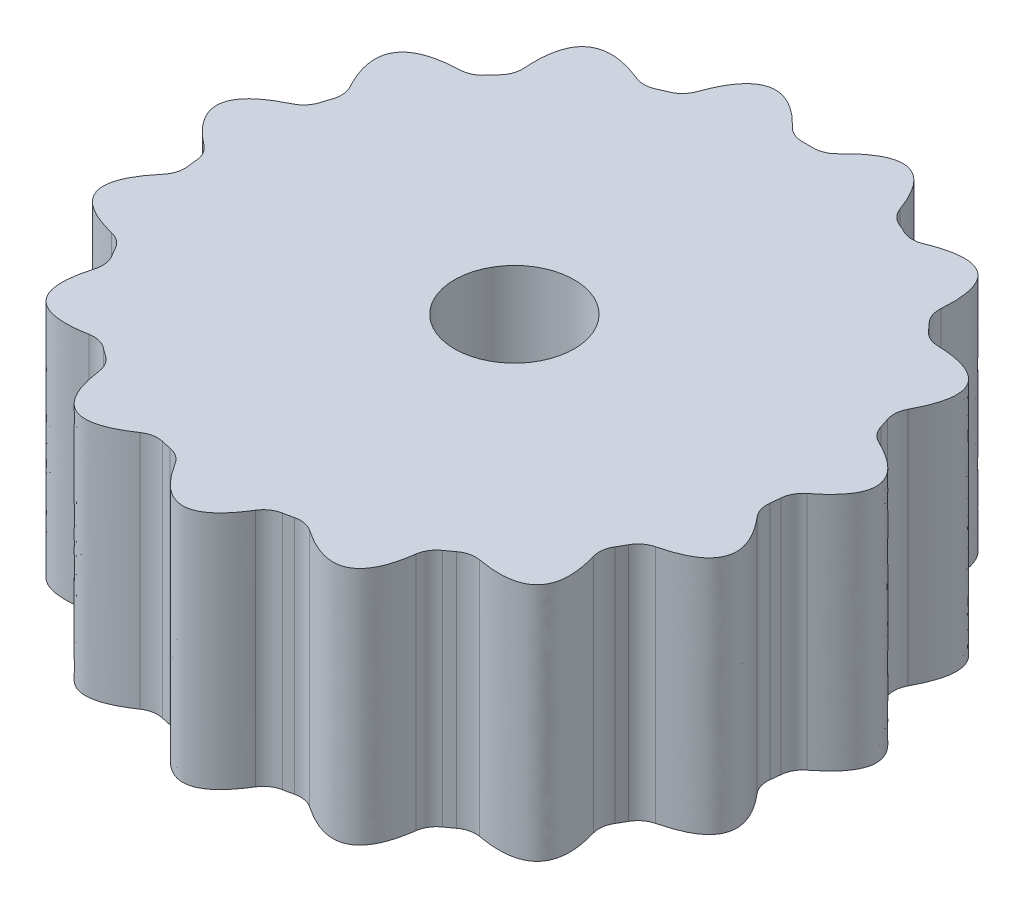
SolidWorks part; units mm, degrees
ref_plane "Front Plane" through (0, 0, 0) normal (0, 0, 1) x (1, 0, 0)
ref_plane "Top Plane" through (0, 0, 0) normal (0, 1, 0) x (1, 0, 0)
ref_plane "Right Plane" through (0, 0, 0) normal (1, 0, 0) x (0, 0, -1)
sketch "Sketch1" plane through (0, 0, 0) normal (0, 1, 0) x (1, 0, 0)
  circle A0 centre (0, 0) radius 12.25
  dimension "D1" = 24.5
extrude "Boss-Extrude1" add sketch "Sketch1" along normal blind 10
sketch "Sketch3" plane through (0, 0, 0) normal (0, 1, 0) x (1, 0, 0)
  line L0 (0, -5.5) -> (0, 5.5) construction
  circle A0 centre (0, 0) radius 12.25 construction
  arc A1 (-1.9, -12.1018) -> (1.9, -12.1018) centre (0, 0) ccw
  spline S0 degree 2 poles (-1.9, -12.1018) (0, -15.5782) (1.9, -12.1018) knots 0 0 0 1 1 1
  point P0 (-1.9, -12.1018)
  point P5 (1.9, -12.1018)
  point P6 (0, -13.84)
  point P12 (0, 0)
  dimension "D4" = 1.9
  dimension "D1" = 1.9
  dimension "D2" = 1.9
  dimension "D3" = 13.84
extrude "Boss-Extrude2" add sketch "Sketch3" along normal up to surface (10 mm away) contours S0 A1 up to face at (0, 10, 12.25)
pattern_circular "CirPattern1" count 15 over 360 about axis through (0, 10, 0) along (0, 1, 0) of "Boss-Extrude2"
fillet "Fillet1" radius 1 30 edges at (-5.5761, 5, -10.9073) (-8.6504, 5, -8.6737) (-0.6576, 5, -12.2323) (-4.3746, 5, -11.4423) (4.3746, 5, -11.4423) (0.6576, 5, -12.2323) (8.6504, 5, -8.6737) (5.5761, 5, -10.9073) (11.4304, 5, -4.4054) (9.5304, 5, -7.6963) (12.2341, 5, 0.6246) (11.8369, 5, -3.1546) (10.9223, 5, 5.5467) (12.0966, 5, 1.9326) (7.722, 5, 9.5096) (10.2647, 5, 6.6857) (3.1865, 5, 11.8283) (6.658, 5, 10.2827) (-1.9, 5, 12.1018) (1.9, 5, 12.1018) (-6.658, 5, 10.2827) (-3.1865, 5, 11.8283) (-10.2647, 5, 6.6857) (-7.722, 5, 9.5096) (-12.0966, 5, 1.9326) (-10.9223, 5, 5.5467) (-11.8369, 5, -3.1546) (-12.2341, 5, 0.6246) (-9.5304, 5, -7.6963) (-11.4304, 5, -4.4054)
sketch "Sketch4" plane through (0, 10, 0) normal (0, 1, 0) x (1, 0, 0)
  circle A0 centre (0, 0) radius 2.5
  dimension "D1" = 5
extrude "Cut-Extrude1" cut sketch "Sketch4" against normal through all
